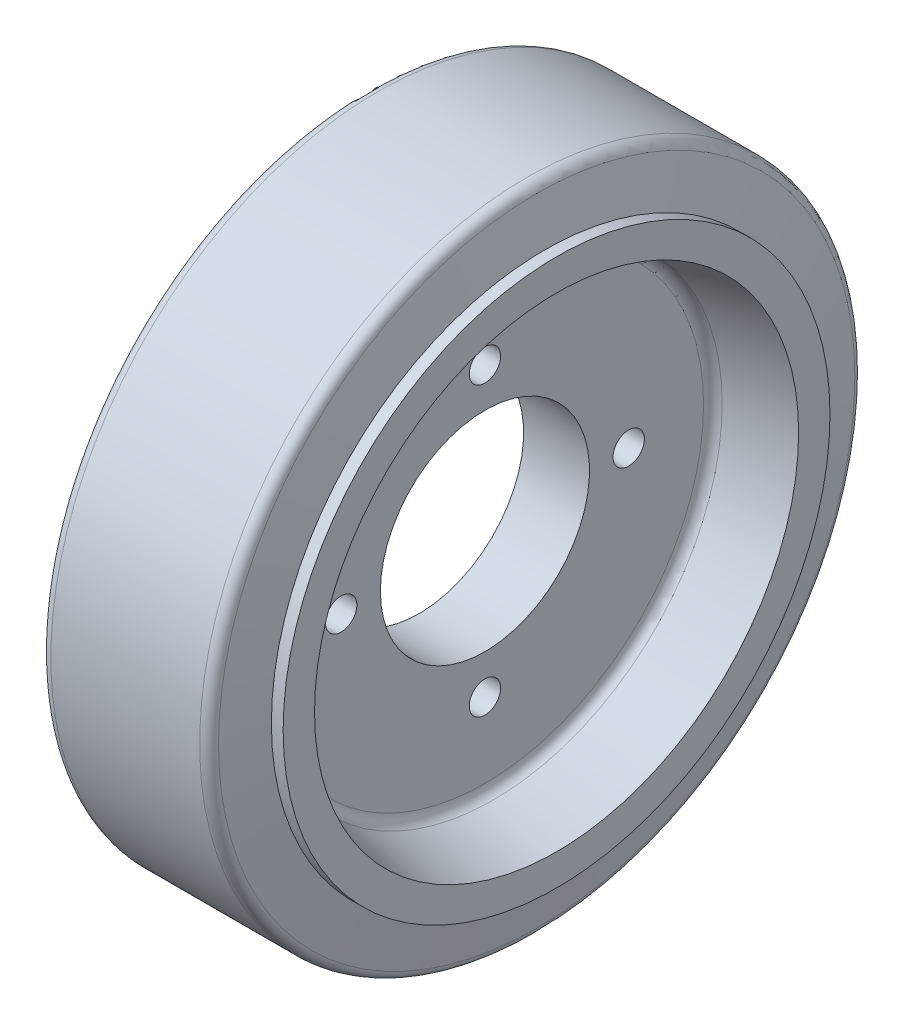
SolidWorks part; units mm, degrees
material "PUR"
ref_plane "Front Plane" through (0, 0, 0) normal (0, 0, 1) x (1, 0, 0)
ref_plane "Top Plane" through (0, 0, 0) normal (0, 1, 0) x (1, 0, 0)
ref_plane "Right Plane" through (0, 0, 0) normal (1, 0, 0) x (0, 0, -1)
sketch "Sketch1" plane through (0, 0, 0) normal (0, 0, 1) x (1, 0, 0)
  line L0 (-15.9, -62.5) -> (15.9, -62.5)
  line L1 (-15.9, -62.5) -> (-17.75, -52.3)
  line L2 (20, -46.3) -> (6.3, -43.45)
  line L3 (6.3, -43.45) -> (6.3, -17)
  line L4 (6.3, -17) -> (22.2, -15.75)
  line L5 (22.2, -15.75) -> (22.2, -10.05)
  line L6 (0, -62.5) -> (0, 0) construction
  line L7 (0, 0) -> (22.2, 0) construction
  line L8 (22.2, -10.05) -> (-22.2, -10.05)
  line L9 (-22.2, -15.75) -> (-22.2, -10.05)
  line L10 (-6.3, -17) -> (-22.2, -15.75)
  line L11 (-6.3, -43.45) -> (-6.3, -17)
  line L12 (-20, -46.3) -> (-6.3, -43.45)
  line L13 (-17.75, -52.3) -> (-20, -52.3)
  line L14 (-20, -52.3) -> (-20, -46.3)
  line L15 (15.9, -62.5) -> (17.75, -52.3)
  line L16 (17.75, -52.3) -> (20, -52.3)
  line L17 (20, -52.3) -> (20, -46.3)
  point P12 (0, -10.05)
  dimension "D1" = 44.4
  dimension "D2" = 40
  dimension "D3" = 20.1
  dimension "D4" = 31.5
  dimension "D5" = 125
  dimension "D6" = 6
  dimension "D7" = 15.9
  dimension "D8" = 1.85
  dimension "D9" = 2.25
  dimension "D10" = 16.2
  dimension "D11" = 2.85
  dimension "D12" = 34
revolve "Revolve1" add sketch "Sketch1" angle 360 about L7
fillet "Fillet1" radius 2 8 edges at (6.3, 0, 43.45) (6.3, 0, 17) (-6.3, 0, 17) (-6.3, 0, 43.45) (22.2, 0, 15.75) (-22.2, 0, 15.75) (-15.9, 0, 62.5) (15.9, 0, 62.5)
sketch "Sketch2" plane through (-6.3, 0, 0) normal (-1, 0, 0) x (0, 0, 1)
  circle A0 centre (0, 0) radius 20
  dimension "D1" = 40
extrude "Cut-Extrude1" cut sketch "Sketch2" against normal through all both and the other way through all
sketch "Sketch3" plane through (-6.3, 0, 0) normal (-1, 0, 0) x (0, 0, 1)
  circle A0 centre (0, 27.5) radius 3
  circle A1 centre (-27.5, 0) radius 3
  circle A2 centre (0, -27.5) radius 3
  circle A3 centre (27.5, 0) radius 3
  circle A4 centre (0, 0) radius 27.5 construction
  dimension "D1" = 55
  dimension "D2" = 6
extrude "Cut-Extrude2" cut sketch "Sketch3" against normal through all
move or copy body "Body-Move/Copy1" [suppressed] bodies to move or copy 101
